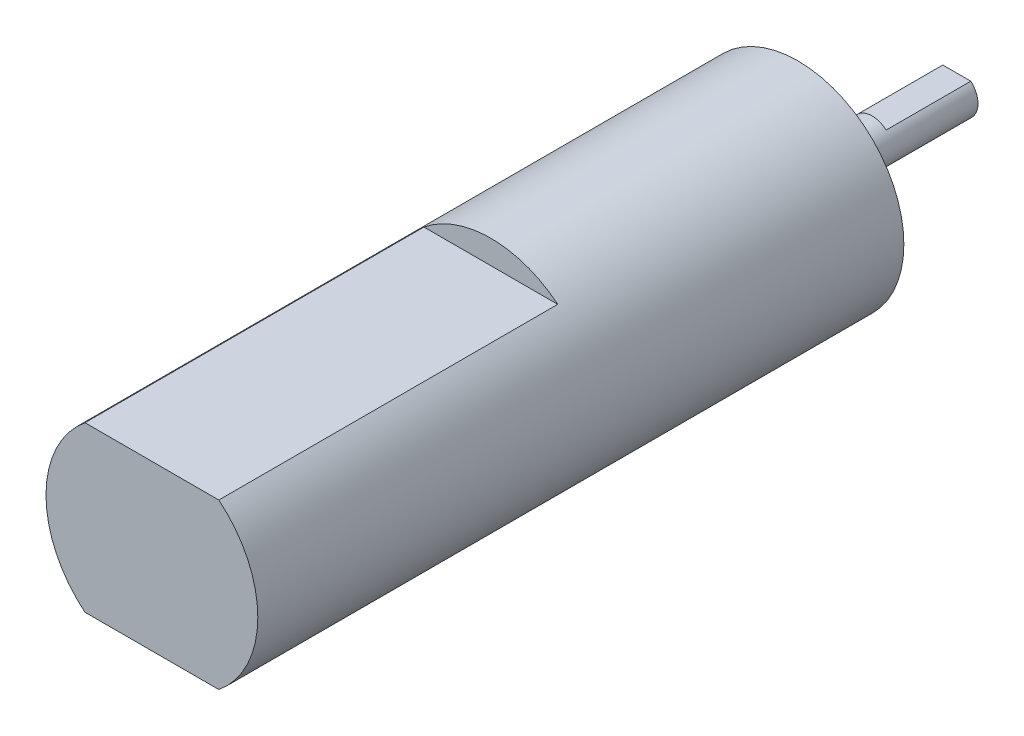
SolidWorks part; units mm, degrees
ref_plane "Front Plane" through (0, 0, 0) normal (0, 0, 1) x (1, 0, 0)
ref_plane "Top Plane" through (0, 0, 0) normal (0, 1, 0) x (1, 0, 0)
ref_plane "Right Plane" through (0, 0, 0) normal (1, 0, 0) x (0, 0, -1)
sketch "Sketch1" plane through (0, 0, 0) normal (0, 0, 1) x (1, 0, 0)
  circle A0 centre (0, 0) radius 10
  dimension "D1" = 20
extrude "Boss-Extrude1" add sketch "Sketch1" along normal blind 32 and the other way blind 29
sketch "Sketch2" plane through (0, 0, 32) normal (0, 0, 1) x (1, 0, 0)
  line L0 (-10, 0) -> (10, 0) construction
  line L1 (-6.3196, 7.75) -> (6.3196, 7.75)
  line L2 (6.3196, -7.75) -> (-6.3196, -7.75)
  circle A0 centre (0, 0) radius 10
  circle A1 centre (0, 0) radius 10 construction
  circle M4 centre (0, 0) radius 10
  dimension "D1" = 15.5
extrude "Cut-Extrude1" cut sketch "Sketch2" against normal up to surface (32 mm away) contours L2 M4 | L1 M4
sketch "Sketch3" plane through (0, 0, -29) normal (0, 0, -1) x (-1, 0, 0)
  circle A0 centre (0, 0) radius 5
  dimension "D1" = 10
extrude "Boss-Extrude2" add sketch "Sketch3" along normal blind 2
sketch "Sketch4" plane through (0, 0, -31) normal (0, 0, -1) x (-1, 0, 0)
  circle A0 centre (0, 0) radius 2
  dimension "D1" = 4
extrude "Boss-Extrude3" add sketch "Sketch4" along normal blind 13
sketch "Sketch5" plane through (0, 0, -44) normal (0, 0, -1) x (-1, 0, 0)
  line L0 (-1.3229, 1.5) -> (1.3229, 1.5)
  line L1 (0, 2) -> (0, -2) construction
  circle A0 centre (0, 0) radius 2
  circle A1 centre (0, 0) radius 2 construction
  circle M2 centre (0, 0) radius 2
  dimension "D1" = 3.5
extrude "Cut-Extrude2" cut sketch "Sketch5" against normal blind 8 contours L1 L0 M2 | L1 A0 L0
